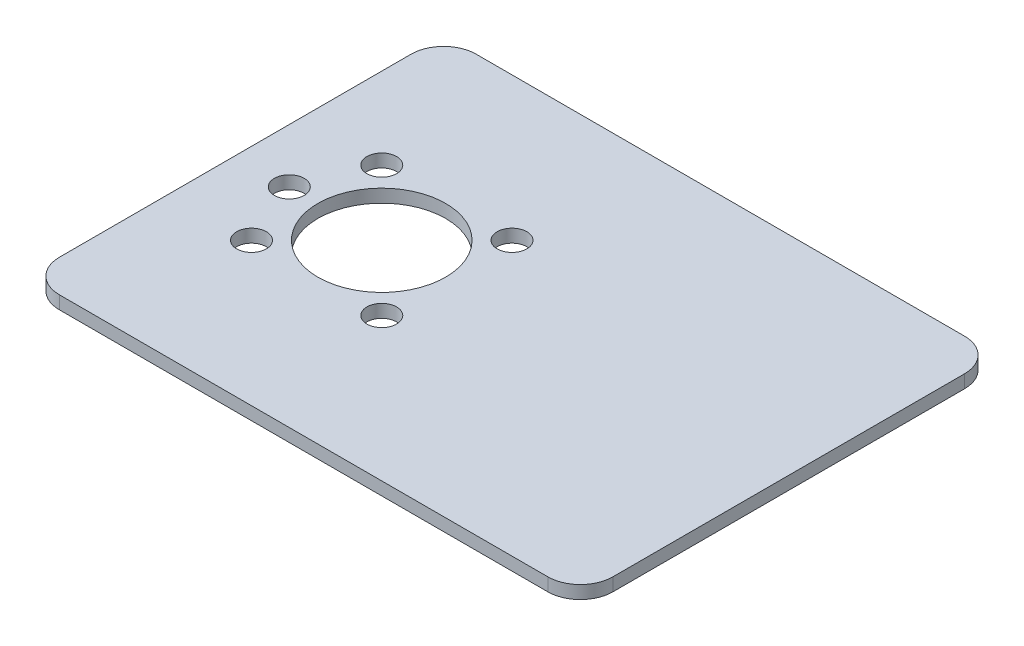
SolidWorks part; units mm, degrees
material "6061 Alloy"
ref_plane "Front Plane" through (0, 0, 0) normal (0, 0, 1) x (1, 0, 0)
ref_plane "Top Plane" through (0, 0, 0) normal (0, 1, 0) x (1, 0, 0)
ref_plane "Right Plane" through (0, 0, 0) normal (1, 0, 0) x (0, 0, -1)
sketch "Sketch1" plane through (0, 0, 0) normal (0, 1, 0) x (1, 0, 0)
  line L0 (0, 40.64) -> (107.95, 40.64) construction
  line L5 (0, 0) -> (107.95, 0)
  line L6 (0, 0) -> (0, 81.28)
  line L7 (0, 81.28) -> (107.95, 81.28)
  line L8 (107.95, 0) -> (107.95, 81.28)
  line L9 (15.875, 53.34) -> (41.275, 53.34) construction
  line L10 (15.875, 53.34) -> (15.875, 27.94) construction
  line L11 (15.875, 27.94) -> (41.275, 27.94) construction
  line L12 (41.275, 53.34) -> (41.275, 27.94) construction
  line L13 (28.575, 53.34) -> (28.575, 27.94) construction
  point P10 (15.875, 40.64)
  point P12 (28.575, 40.64)
  point P17 (107.95, 40.64)
  dimension "D1" = 107.95
  dimension "D2" = 81.28
  dimension "D3" = 25.4
  dimension "D5" = 15.875
extrude "Boss-Extrude1" add sketch "Sketch1" along normal blind 2.54
sketch "Sketch4" plane through (0, 2.54, 0) normal (0, 1, 0) x (1, 0, 0)
  line L0 (0, 40.64) -> (107.95, 40.64) construction
  point P0 (15.875, 53.34)
  point P3 (41.275, 53.34)
  point P6 (41.275, 27.94)
  point P9 (15.875, 27.94)
  point P28 (10.541, 40.64)
  dimension "D1" = 18.034
hole_wizard "M5 Clearance Hole1" positions "Sketch4" profile "Sketch3" hole size "M5" standard "ANSI Metric" end condition up to next
sketch "Sketch3" plane through (15.875, 2.54, -53.34) normal (1, 0, 0) x (0, 0, 1)
  line L0 (0, 0) -> (0, 2.54)
  line L1 (0, 2.54) -> (2.9, 2.54)
  line L2 (2.9, 2.54) -> (2.9, 0)
  line L5 (2.9, 0) -> (0, 0)
  line L11 (0, -6.35) -> (0, 107.95) construction
  dimension "Thru Hole Dia." = 5.8
  dimension "Thru Hole Depth" = 2.54
sketch "Sketch9" plane through (0, 2.54, 0) normal (0, 1, 0) x (1, 0, 0)
  point P0 (28.575, 40.64)
hole_wizard "#97 (0.981) Diameter Hole1" positions "Sketch9" profile "Sketch8" hole size "#97" standard "ANSI Inch" end condition up to next
sketch "Sketch8" plane through (28.575, 2.54, -40.64) normal (1, 0, 0) x (0, 0, 1)
  line L0 (0, 0) -> (0, 2.54)
  line L1 (0, 2.54) -> (12.4587, 2.54)
  line L2 (12.4587, 2.54) -> (12.4587, 0)
  line L5 (12.4587, 0) -> (0, 0)
  line L11 (0, -6.35) -> (0, 107.95) construction
  dimension "Thru Hole Dia." = 24.9174
  dimension "Thru Hole Depth" = 2.54
fillet "Fillet1" radius 6.35 4 edges at (0, 1.27, -81.28) (0, 1.27, 0) (107.95, 1.27, 0) (107.95, 1.27, -81.28)
sketch "Sketch10" plane through (0, 2.54, 0) normal (0, 1, 0) x (1, 0, 0)
  line L0 (28.575, 40.64) -> (51.075, 40.64)
  dimension "D1" = 22.5
